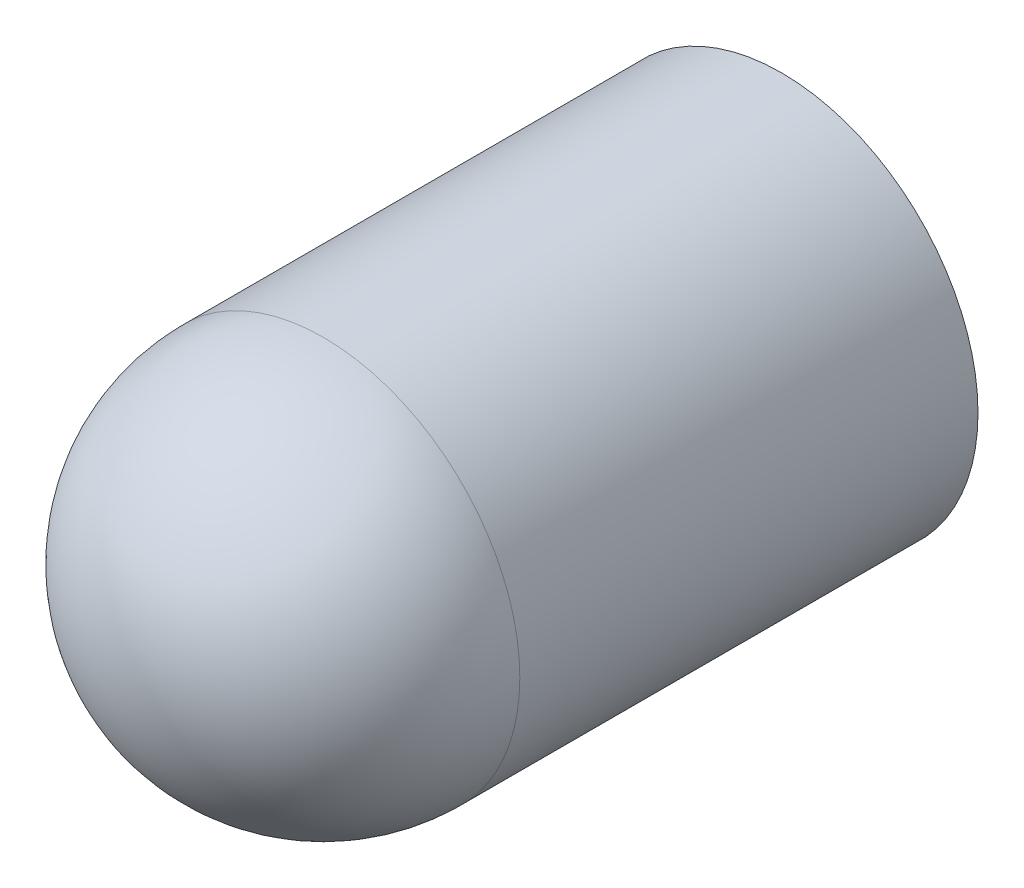
SolidWorks part; units mm, degrees
ref_plane "Plan de face" through (0, 0, 0) normal (0, 0, 1) x (1, 0, 0)
ref_plane "Plan de dessus" through (0, 0, 0) normal (0, 1, 0) x (1, 0, 0)
ref_plane "Plan de droite" through (0, 0, 0) normal (1, 0, 0) x (0, 0, -1)
sketch "Esquisse1" plane through (0, 0, 0) normal (0, 0, 1) x (1, 0, 0)
  circle A0 centre (5.7355, -24.3761) radius 1.5
  dimension "D1" = 3
extrude "Boss.-Extru.1" add sketch "Esquisse1" along normal blind 1.5 and the other way blind 2
sketch "Esquisse2" plane through (0, 0, 1.5) normal (0, 0, 1) x (1, 0, 0)
  line L0 (5.7355, -25.8761) -> (5.7355, -22.8761)
  circle A0 centre (5.7355, -24.3761) radius 1.5 construction
  arc A1 (5.7355, -22.8761) -> (5.7355, -25.8761) centre (5.7355, -24.3761) ccw
revolve "Révolution1" add sketch "Esquisse2" angle 180 about L0
